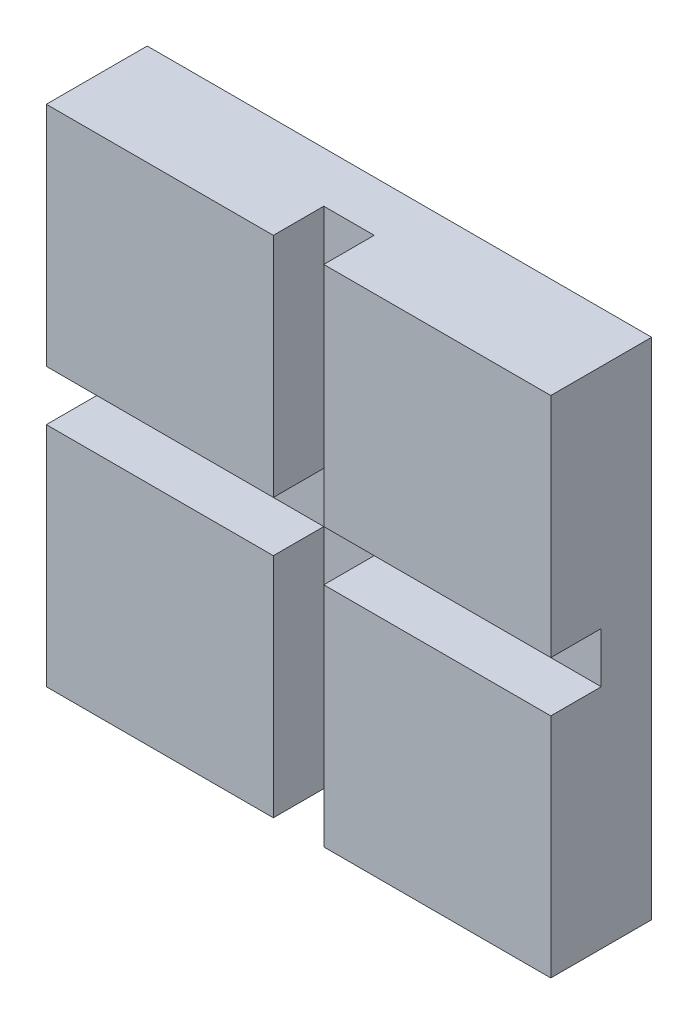
SolidWorks part; units mm, degrees
ref_plane "Front Plane" through (0, 0, 0) normal (0, 0, 1) x (1, 0, 0)
ref_plane "Top Plane" through (0, 0, 0) normal (0, 1, 0) x (1, 0, 0)
ref_plane "Right Plane" through (0, 0, 0) normal (1, 0, 0) x (0, 0, -1)
sketch "Sketch1" plane through (0, 0, 0) normal (0, 0, 1) x (1, 0, 0)
  line L1 (50, -50) -> (-50, -50)
  line L2 (50, -50) -> (50, 50)
  line L3 (50, 50) -> (-50, 50)
  line L4 (-50, -50) -> (-50, 50)
  line L5 (50, -50) -> (-50, 50) construction
  line L6 (50, 50) -> (-50, -50) construction
  point P0 (0, 0)
  dimension "D1" = 100
extrude "Extrude1" add sketch "Sketch1" against normal blind 20
sketch "Sketch2" plane through (0, 0, 0) normal (0, 0, 1) x (1, 0, 0)
  line L0 (0, 50) -> (0, -50) construction
  line L1 (50, 50) -> (-50, 50) construction
  line L2 (-50, -50) -> (50, -50) construction
  line L3 (-50, 0) -> (50, 0) construction
  line L4 (-50, 50) -> (-50, -50) construction
  line L5 (50, -50) -> (50, 50) construction
  line L7 (50, -5) -> (-50, -5)
  line L8 (50, -5) -> (50, 5)
  line L9 (50, 5) -> (-50, 5)
  line L10 (-50, -5) -> (-50, 5)
  line L11 (50, -5) -> (-50, 5) construction
  line L12 (50, 5) -> (-50, -5) construction
  line L13 (-5, -50) -> (5, -50)
  line L14 (-5, -50) -> (-5, 50)
  line L15 (-5, 50) -> (5, 50)
  line L16 (5, -50) -> (5, 50)
  line L17 (-5, -50) -> (5, 50) construction
  line L18 (-5, 50) -> (5, -50) construction
  point P12 (0, 0)
  point P18 (0, 0)
  dimension "D1" = 10
  dimension "D2" = 10
extrude "Extrude2" cut sketch "Sketch2" against normal blind 10 contours L16 L15 L14 L13
sketch "Sketch3" plane through (0, 0, 0) normal (0, 0, 1) x (1, 0, 0)
  line L0 (-50, 0) -> (50, 0) construction
  line L1 (-50, 50) -> (-50, -50) construction
  line L2 (50, -50) -> (50, 50) construction
  line L4 (50, -5) -> (-50, -5)
  line L5 (50, -5) -> (50, 5)
  line L6 (50, 5) -> (-50, 5)
  line L7 (-50, -5) -> (-50, 5)
  line L8 (50, -5) -> (-50, 5) construction
  line L9 (50, 5) -> (-50, -5) construction
  point P6 (0, 0)
  dimension "D1" = 10
extrude "Extrude3" cut sketch "Sketch3" against normal blind 10
